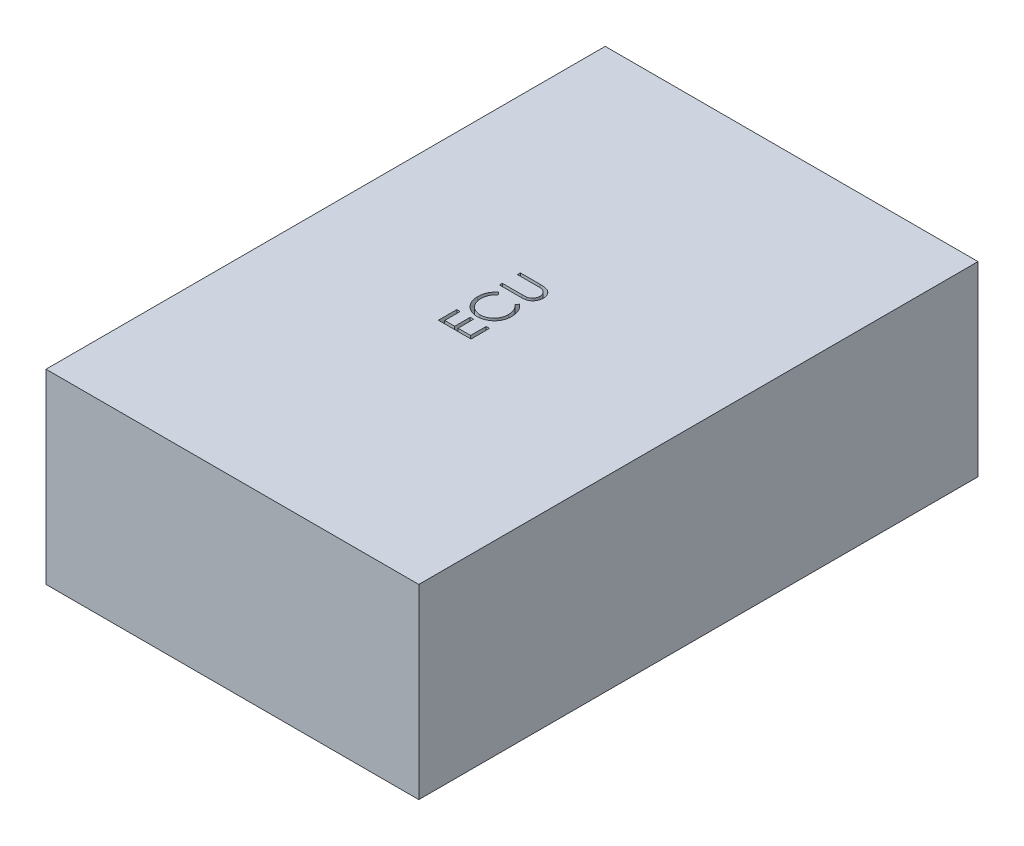
SolidWorks part; units mm, degrees
ref_plane "Front Plane" through (0, 0, 0) normal (0, 0, 1) x (1, 0, 0)
ref_plane "Top Plane" through (0, 0, 0) normal (0, 1, 0) x (1, 0, 0)
ref_plane "Right Plane" through (0, 0, 0) normal (1, 0, 0) x (0, 0, -1)
sketch "Sketch2" plane through (0, 0, 0) normal (0, 1, 0) x (1, 0, 0)
  line L1 (-20, 30) -> (20, 30)
  line L2 (-20, 30) -> (-20, -30)
  line L3 (-20, -30) -> (20, -30)
  line L4 (20, 30) -> (20, -30)
  line L5 (-20, 30) -> (20, -30) construction
  line L6 (-20, -30) -> (20, 30) construction
  point P0 (0, 0)
  dimension "D1" = 40
  dimension "D2" = 60
extrude "Boss-Extrude1" add sketch "Sketch2" along normal blind 20
sketch "Sketch3" plane through (0, 20, 0) normal (0, 1, 0) x (1, 0, 0)
  line L0 (0, -30) -> (0, 30) construction
  line L1 (-20, -30) -> (20, -30) construction
  line L2 (20, 30) -> (-20, 30) construction
  text T0 "ECU" font "Century Gothic" height 3.5
extrude "Cut-Extrude1" cut sketch "Sketch3" against normal blind 2
